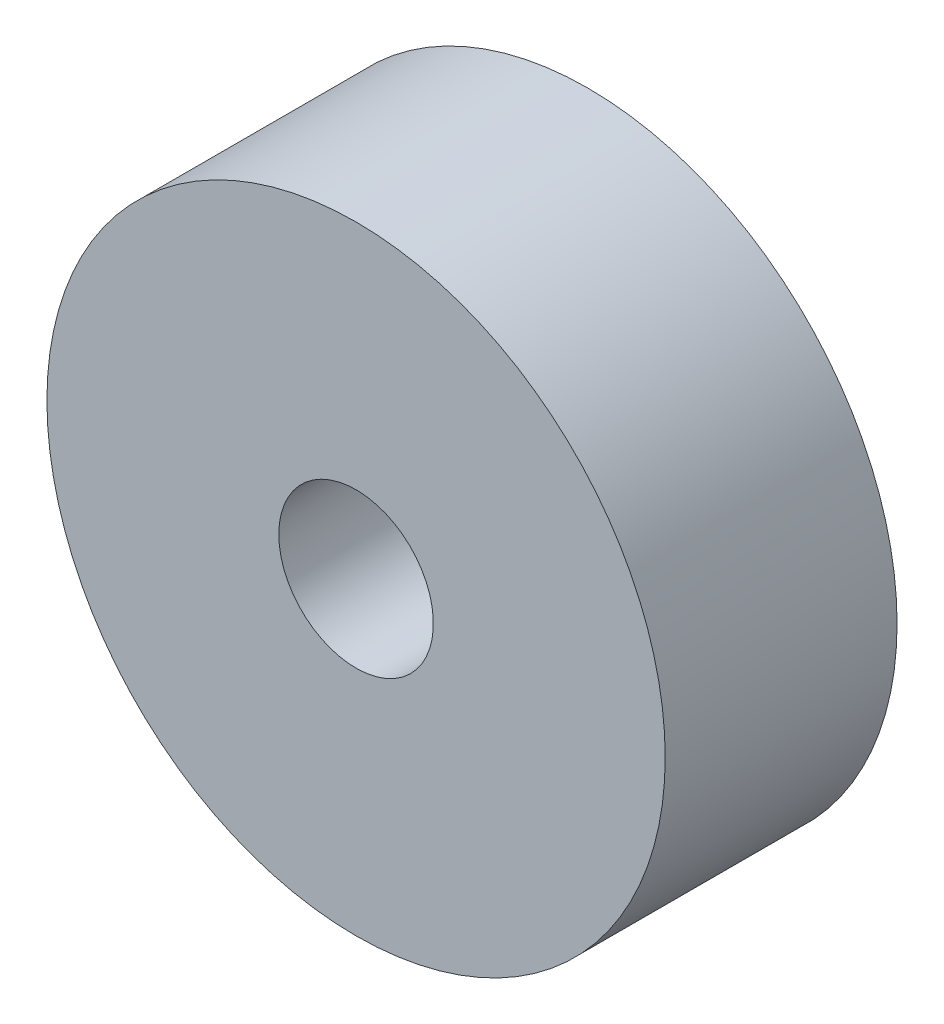
SolidWorks part; units mm, degrees
ref_plane "Front Plane" through (0, 0, 0) normal (0, 0, 1) x (1, 0, 0)
ref_plane "Top Plane" through (0, 0, 0) normal (0, 1, 0) x (1, 0, 0)
ref_plane "Right Plane" through (0, 0, 0) normal (1, 0, 0) x (0, 0, -1)
sketch "Sketch1" plane through (0, 0, 0) normal (0, 0, 1) x (1, 0, 0)
  circle A0 centre (0, 0) radius 50.8
  circle A1 centre (0, 0) radius 12.7
  dimension "D1" = 101.6
  dimension "D2" = 25.4
extrude "Boss-Extrude1" add sketch "Sketch1" along normal blind 38.1
equation "\"Thick\"= \"in\""
